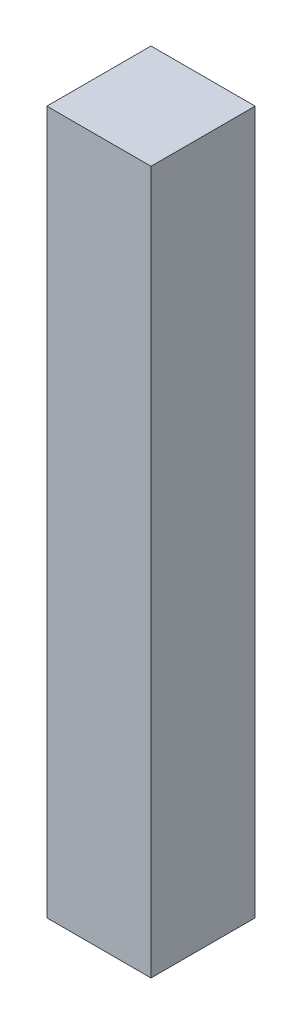
SolidWorks part; units mm, degrees
ref_plane "前视基准面" through (0, 0, 0) normal (0, 0, 1) x (1, 0, 0)
ref_plane "上视基准面" through (0, 0, 0) normal (0, 1, 0) x (1, 0, 0)
ref_plane "右视基准面" through (0, 0, 0) normal (1, 0, 0) x (0, 0, -1)
sketch "草图1" plane through (0, 0, 0) normal (0, 0, 1) x (1, 0, 0)
  line L1 (0, 1.626) -> (0.8, 1.626)
  line L2 (0, 1.626) -> (0, -3.774)
  line L3 (0, -3.774) -> (0.8, -3.774)
  line L4 (0.8, 1.626) -> (0.8, -3.774)
  dimension "D1" = 0.8
  dimension "D2" = 5.4
extrude "凸台-拉伸1" add sketch "草图1" along normal blind 0.8
